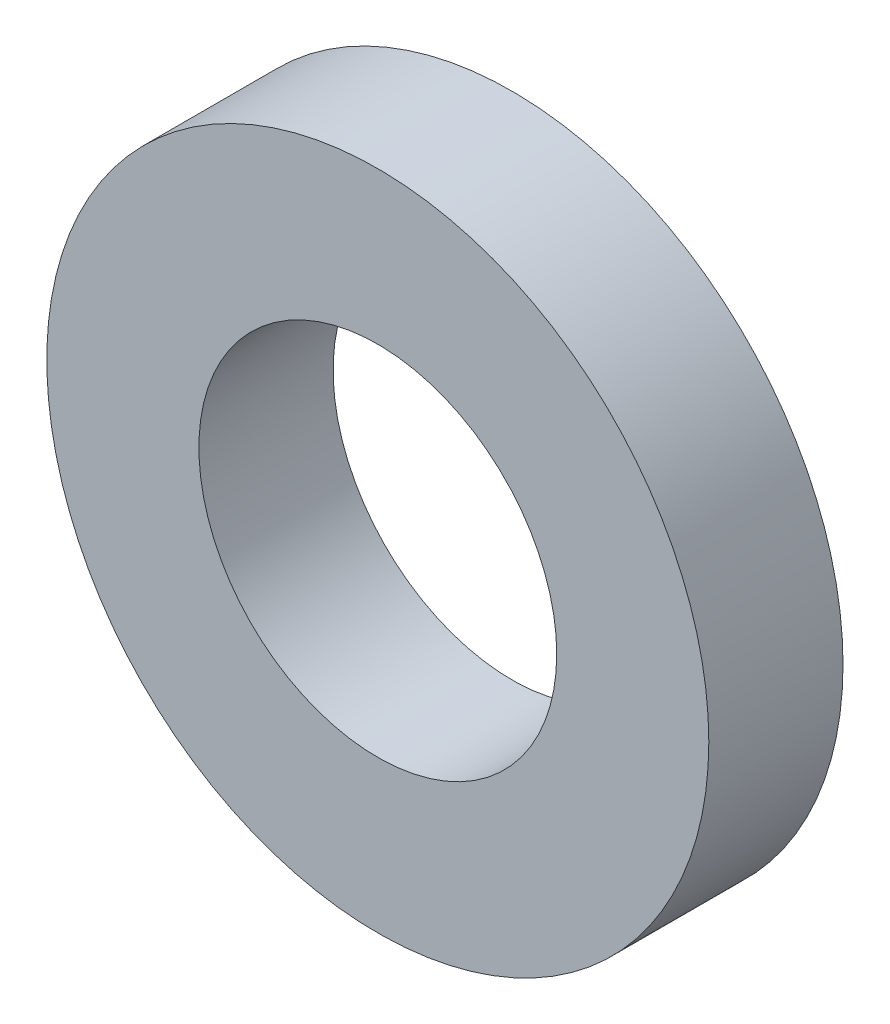
SolidWorks part; units mm, degrees
material "PET"
ref_plane "Piano frontale" through (0, 0, 0) normal (0, 0, 1) x (1, 0, 0)
ref_plane "Piano superiore" through (0, 0, 0) normal (0, 1, 0) x (1, 0, 0)
ref_plane "Piano destro" through (0, 0, 0) normal (1, 0, 0) x (0, 0, -1)
sketch "Schizzo1" plane through (0, 0, 0) normal (0, 0, 1) x (1, 0, 0)
  circle A0 centre (0, 0) radius 4
  circle A1 centre (0, 0) radius 7.4
  dimension "D1" = 8
  dimension "D2" = 14.8
extrude "Estrusione-Estrusione1" add sketch "Schizzo1" along normal blind 3
